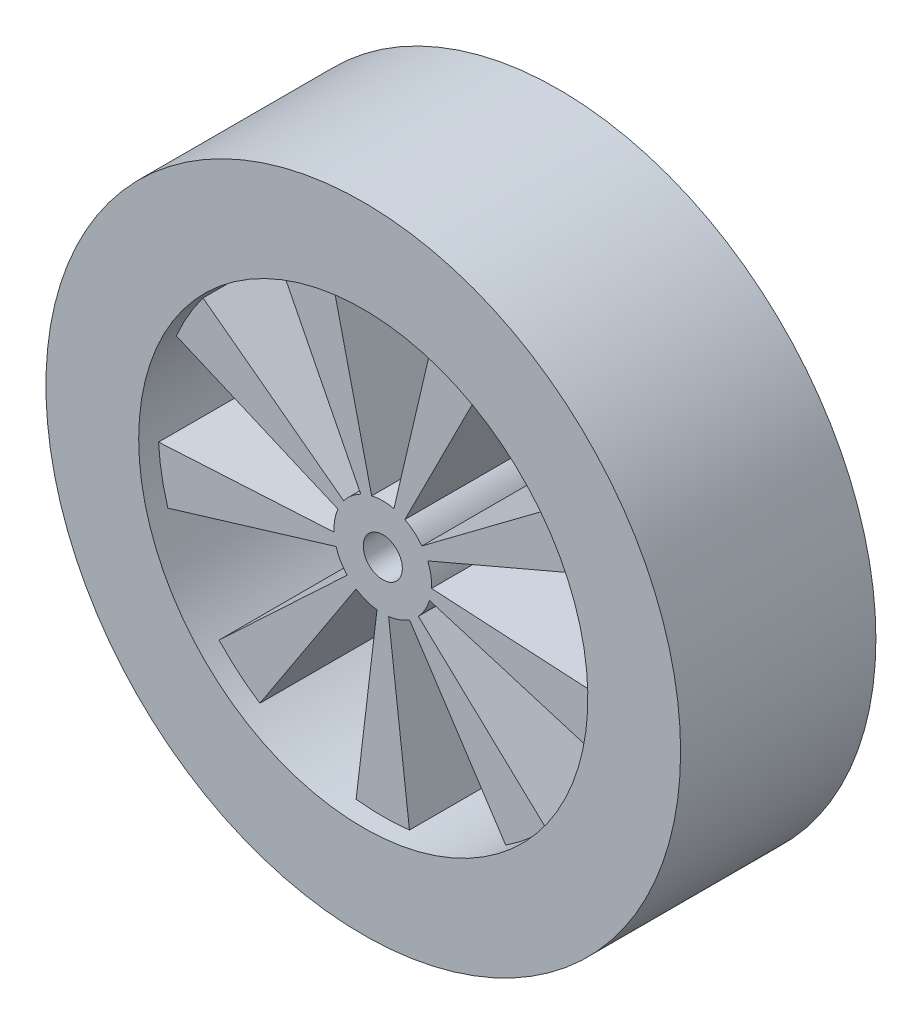
SolidWorks part; units mm, degrees
ref_plane "Alzado" through (0, 0, 0) normal (0, 0, 1) x (1, 0, 0)
ref_plane "Planta" through (0, 0, 0) normal (0, 1, 0) x (1, 0, 0)
ref_plane "Vista lateral" through (0, 0, 0) normal (1, 0, 0) x (0, 0, -1)
sketch "Croquis1" plane through (0, 0, 0) normal (0, 0, 1) x (1, 0, 0)
  circle A0 centre (0, 0) radius 32.5
extrude "Saliente-Extruir1" add sketch "Croquis1" along normal blind 20
sketch "Croquis2" plane through (0, 0, 0) normal (0, 0, -1) x (-1, 0, 0)
  circle A0 centre (0, 0) radius 2
extrude "Cortar-Extruir1" cut sketch "Croquis2" against normal blind 20
sketch "Croquis3" plane through (0, 0, 20) normal (0, 0, 1) x (1, 0, 0)
  line L0 (1.1401, 4.8683) -> (5.2446, 22.3941)
  line L1 (-1.1401, 4.8683) -> (-5.2446, 22.3941)
  line L2 (4.0027, 2.9964) -> (18.4122, 13.7837)
  line L3 (2.2559, 4.4622) -> (10.377, 20.526)
  line L4 (4.9923, -0.2774) -> (22.9646, -1.2763)
  line L5 (4.5963, 1.9682) -> (21.1431, 9.0536)
  line L6 (3.646, -3.4215) -> (16.7715, -15.739)
  line L7 (4.7861, -1.4467) -> (22.0161, -6.655)
  line L8 (0.5937, -4.9646) -> (2.7309, -22.8373)
  line L9 (2.7364, -4.1847) -> (12.5876, -19.2498)
  line L10 (-2.7364, -4.1847) -> (-12.5876, -19.2498)
  line L11 (-0.5937, -4.9646) -> (-2.7309, -22.8373)
  line L12 (-4.7861, -1.4467) -> (-22.0161, -6.655)
  line L13 (-3.646, -3.4215) -> (-16.7715, -15.739)
  line L14 (-4.5963, 1.9682) -> (-21.1431, 9.0536)
  line L15 (-4.9923, -0.2774) -> (-22.9646, -1.2763)
  line L16 (-2.2559, 4.4622) -> (-10.377, 20.526)
  line L17 (-4.0027, 2.9964) -> (-18.4122, 13.7837)
  circle A0 centre (0, 0) radius 23 construction
  circle A1 centre (0, 0) radius 5 construction
  arc A2 (-5.2446, 22.3941) -> (5.2446, 22.3941) centre (0, 0) cw
  arc A3 (-1.1401, 4.8683) -> (1.1401, 4.8683) centre (0, 0) cw
  arc A4 (2.2559, 4.4622) -> (4.0027, 2.9964) centre (0, 0) cw
  arc A5 (10.377, 20.526) -> (18.4122, 13.7837) centre (0, 0) cw
  arc A6 (4.5963, 1.9682) -> (4.9923, -0.2774) centre (0, 0) cw
  arc A7 (21.1431, 9.0536) -> (22.9646, -1.2763) centre (0, 0) cw
  arc A8 (4.7861, -1.4467) -> (3.646, -3.4215) centre (0, 0) cw
  arc A9 (22.0161, -6.655) -> (16.7715, -15.739) centre (0, 0) cw
  arc A10 (2.7364, -4.1847) -> (0.5937, -4.9646) centre (0, 0) cw
  arc A11 (12.5876, -19.2498) -> (2.7309, -22.8373) centre (0, 0) cw
  arc A12 (-0.5937, -4.9646) -> (-2.7364, -4.1847) centre (0, 0) cw
  arc A13 (-2.7309, -22.8373) -> (-12.5876, -19.2498) centre (0, 0) cw
  arc A14 (-3.646, -3.4215) -> (-4.7861, -1.4467) centre (0, 0) cw
  arc A15 (-16.7715, -15.739) -> (-22.0161, -6.655) centre (0, 0) cw
  arc A16 (-4.9923, -0.2774) -> (-4.5963, 1.9682) centre (0, 0) cw
  arc A17 (-22.9646, -1.2763) -> (-21.1431, 9.0536) centre (0, 0) cw
  arc A18 (-4.0027, 2.9964) -> (-2.2559, 4.4622) centre (0, 0) cw
  arc A19 (-18.4122, 13.7837) -> (-10.377, 20.526) centre (0, 0) cw
  point P44 (0, 0)
  dimension "D1" = 9
extrude "Cortar-Extruir2" cut sketch "Croquis3" against normal blind 20
sketch "Croquis4" plane through (0, 0, 20) normal (0, 0, 1) x (1, 0, 0)
  circle A0 centre (0, 0) radius 23
extrude "Cortar-Extruir3" cut sketch "Croquis4" against normal blind 2
